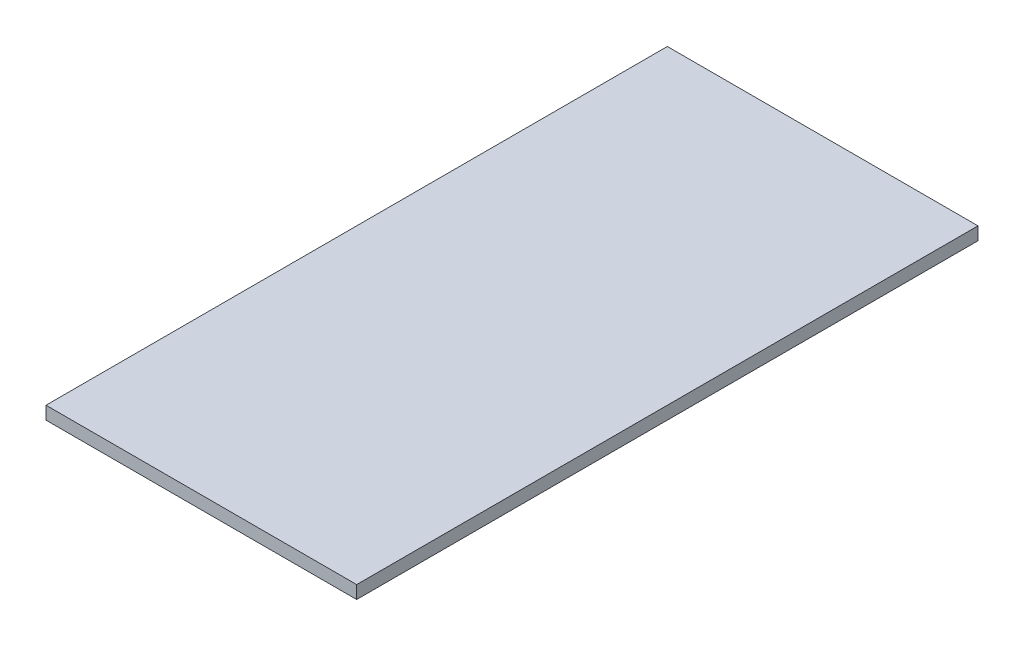
SolidWorks part; units mm, degrees
ref_plane "Front Plane" through (0, 0, 0) normal (0, 0, 1) x (1, 0, 0)
ref_plane "Top Plane" through (0, 0, 0) normal (0, 1, 0) x (1, 0, 0)
ref_plane "Right Plane" through (0, 0, 0) normal (1, 0, 0) x (0, 0, -1)
sketch "Sketch1" plane through (0, 0, 0) normal (0, 1, 0) x (1, 0, 0)
  line L1 (0, 0) -> (76.2, 0)
  line L2 (0, 0) -> (0, 152.4)
  line L3 (0, 152.4) -> (76.2, 152.4)
  line L4 (76.2, 0) -> (76.2, 152.4)
  dimension "D1" = 76.2
  dimension "D2" = 152.4
extrude "Boss-Extrude1" add sketch "Sketch1" along normal blind 3.175
